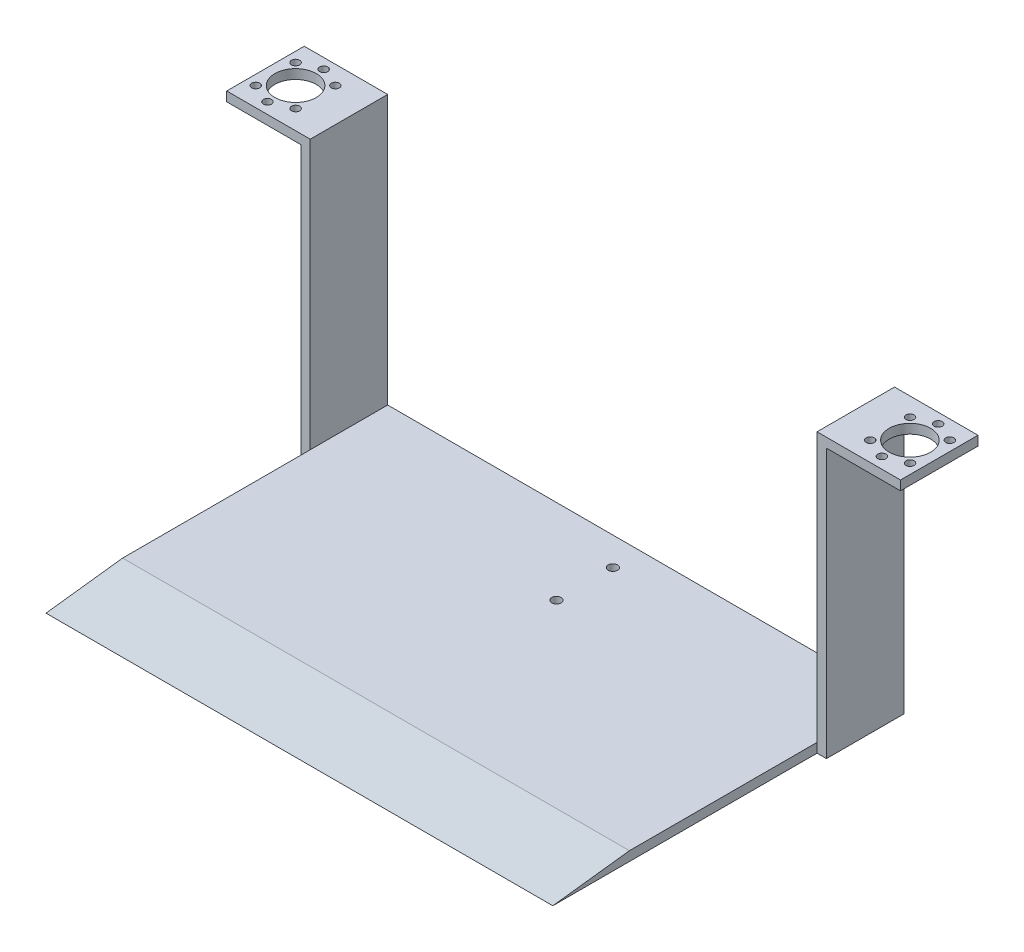
SolidWorks part; units mm, degrees
ref_plane "Front Plane" through (0, 0, 0) normal (0, 0, 1) x (1, 0, 0)
ref_plane "Top Plane" through (0, 0, 0) normal (0, 1, 0) x (1, 0, 0)
ref_plane "Right Plane" through (0, 0, 0) normal (1, 0, 0) x (0, 0, -1)
sketch "Sketch1" plane through (0, 0, 0) normal (0, 1, 0) x (1, 0, 0)
  line L1 (0, 0) -> (454.914, 0)
  line L2 (0, 0) -> (0, 381)
  line L3 (0, 381) -> (454.914, 381)
  line L4 (454.914, 0) -> (454.914, 381)
  dimension "D1" = 454.914
  dimension "D2" = 381
extrude "Boss-Extrude1" add sketch "Sketch1" along normal blind 187.96
sketch "Sketch3" plane through (0, 187.96, 0) normal (0, 1, 0) x (1, 0, 0)
  line L1 (454.914, 0) -> (404.9014, 0)
  line L2 (454.914, 0) -> (454.914, 202.0062)
  line L3 (454.914, 202.0062) -> (404.9014, 202.0062)
  line L4 (404.9014, 0) -> (404.9014, 202.0062)
  line L5 (0, 0) -> (50.0126, 0)
  line L6 (0, 0) -> (0, 202.0062)
  line L7 (0, 202.0062) -> (50.0126, 202.0062)
  line L8 (50.0126, 0) -> (50.0126, 202.0062)
  dimension "D1" = 202.0062
  dimension "D2" = 50.0126
  dimension "D3" = 202.0062
  dimension "D4" = 50.0126
extrude "Cut-Extrude1" cut sketch "Sketch3" against normal through all
sketch "Sketch4" plane through (0, 187.96, 0) normal (0, 1, 0) x (1, 0, 0)
  line L0 (454.914, 381) -> (0, 381) construction
  line L1 (0, 381) -> (0, 202.0062) construction
  line L2 (454.914, 202.0062) -> (454.914, 381) construction
  circle A0 centre (20.066, 355.092) radius 14
  circle A1 centre (434.848, 355.092) radius 14
  dimension "D1" = 28
  dimension "D4" = 28
  dimension "D5" = 20.066
  dimension "D6" = 25.908
  dimension "D2" = 25.908
  dimension "D3" = 20.066
extrude "Cut-Extrude2" cut sketch "Sketch4" against normal through all
sketch "Sketch5" plane through (0, 187.96, 0) normal (0, 1, 0) x (1, 0, 0)
  line L0 (454.914, 381) -> (0, 381) construction
  line L1 (56.3626, 381) -> (398.5514, 381)
  line L2 (56.3626, 381) -> (56.3626, 0)
  line L3 (56.3626, 0) -> (398.5514, 0)
  line L4 (398.5514, 381) -> (398.5514, 0)
  line L5 (50.0126, 0) -> (404.9014, 0) construction
  line L6 (50.0126, 0) -> (50.0126, 202.0062) construction
  line L7 (404.9014, 202.0062) -> (404.9014, 0) construction
  dimension "D1" = 6.35
  dimension "D2" = 6.35
extrude "Cut-Extrude3" cut sketch "Sketch5" against normal blind 181.61
sketch "Sketch6" plane through (454.914, 0, 0) normal (1, 0, 0) x (0, 0, -1)
  line L0 (381, 187.96) -> (381, 0) construction
  line L1 (202.0062, 0) -> (381, 0)
  line L2 (202.0062, 0) -> (202.0062, 181.5974)
  line L3 (202.0062, 181.5974) -> (381, 181.5974)
  line L4 (381, 0) -> (381, 181.5974)
  dimension "D1" = 181.5974
extrude "Cut-Extrude4" cut sketch "Sketch6" against normal blind 50.0126
sketch "Sketch7" plane through (0, 0, 0) normal (-1, 0, 0) x (0, 0, 1)
  line L0 (-202.0062, 0) -> (-202.0062, 187.96) construction
  line L1 (-381, 0) -> (-202.0062, 0)
  line L2 (-381, 0) -> (-381, 181.5974)
  line L3 (-381, 181.5974) -> (-202.0062, 181.5974)
  line L4 (-202.0062, 0) -> (-202.0062, 181.5974)
  dimension "D1" = 181.5974
extrude "Cut-Extrude5" cut sketch "Sketch7" against normal blind 50.0126
sketch "Sketch10" plane through (404.9014, 0, 0) normal (1, 0, 0) x (0, 0, -1)
  line L0 (0, 0) -> (202.0062, 0)
  line L1 (202.0062, 187.96) -> (0, 187.96) construction
  line L3 (202.0062, 187.96) -> (202.0062, 0)
  line L5 (381, 0) -> (0, 0) construction
  line L8 (202.0062, 187.96) -> (0, 187.96)
  line L9 (0, 187.96) -> (0, 0)
  line L10 (202.0062, 181.5974) -> (202.0062, 187.96) construction
extrude "Cut-Extrude6" cut sketch "Sketch10" against normal through all
sketch "Sketch11" plane through (0, 187.96, 0) normal (0, 1, 0) x (1, 0, 0)
  line L0 (434.848, 385.1807) -> (434.848, 325.1677) construction
  line L1 (457.9437, 355.092) -> (408.0384, 355.092) construction
  line L2 (434.848, 355.1742) -> (453.5332, 373.8594) construction
  line L3 (434.848, 355.1742) -> (419.9379, 370.0843) construction
  line L4 (434.848, 355.1742) -> (452.7645, 337.2577) construction
  line L5 (434.848, 355.1742) -> (417.2384, 337.5646) construction
  circle A1 centre (434.848, 374.1742) radius 2.75
  circle A2 centre (448.283, 368.6092) radius 2.75
  circle A3 centre (421.413, 368.6092) radius 2.75
  circle A4 centre (448.283, 341.7392) radius 2.75
  circle A5 centre (434.848, 336.1742) radius 2.75
  circle A6 centre (421.413, 341.7392) radius 2.75
  dimension "D2" = 45
  dimension "D5" = 5.5
  dimension "D6" = 5.5
  dimension "D7" = 5.5
  dimension "D8" = 5.5
  dimension "D9" = 5.5
  dimension "D10" = 5.5
  dimension "D3" = 45
  dimension "D4" = 45
extrude "Cut-Extrude7" cut sketch "Sketch11" against normal through all
sketch "Sketch12" plane through (0, 187.96, 0) normal (0, 1, 0) x (1, 0, 0)
  line L0 (20.066, 355.092) -> (20.066, 379.9549) construction
  line L1 (20.066, 355.092) -> (42.2706, 355.092) construction
  line L2 (20.066, 355.092) -> (20.066, 337.1345) construction
  line L3 (20.066, 355.092) -> (2.8652, 355.092) construction
  line L4 (20.066, 355.092) -> (38.3107, 373.3367) construction
  line L5 (20.066, 355.092) -> (33.6036, 341.5544) construction
  line L6 (20.066, 355.092) -> (5.5449, 369.6131) construction
  line L7 (20.066, 355.092) -> (7.0967, 342.1227) construction
  circle A1 centre (20.066, 374.092) radius 2.75
  circle A2 centre (6.631, 368.527) radius 2.75
  circle A3 centre (33.501, 368.527) radius 2.75
  circle A4 centre (33.501, 341.657) radius 2.75
  circle A5 centre (20.066, 336.092) radius 2.75
  circle A6 centre (6.631, 341.657) radius 2.75
  dimension "D5" = 5.5
  dimension "D6" = 5.5
  dimension "D7" = 5.5
  dimension "D8" = 5.5
  dimension "D9" = 5.5
  dimension "D10" = 5.5
  dimension "D1" = 45
  dimension "D2" = 45
  dimension "45" = 45
  dimension "D3" = 45
extrude "Cut-Extrude8" cut sketch "Sketch12" against normal through all
sketch "Sketch13" plane through (398.5514, 0, 0) normal (1, 0, 0) x (0, 0, -1)
  line L0 (202.0062, 0) -> (150.2896, 0)
  line L1 (150.2896, 0) -> (202.0062, 6.35)
  line L2 (202.0062, 0) -> (202.0062, 181.5974) construction
  line L3 (202.0062, 6.35) -> (202.0062, 0)
  dimension "D1" = 7
  dimension "D2" = 6.35
extrude "Boss-Extrude2" add sketch "Sketch13" against normal up to surface (342.1888 mm away) up to face at (56.3626, 97.155, -291.5031)
sketch "Sketch15" plane through (0, 187.96, 0) normal (0, 1, 0) x (1, 0, 0)
  line L0 (398.5514, 328.676) -> (454.914, 328.676) construction
  line L1 (398.5514, 202.0062) -> (398.5514, 381) construction
  line L2 (454.914, 202.0062) -> (454.914, 381) construction
  line L3 (454.914, 381) -> (398.5514, 381) construction
  line L4 (0, 328.676) -> (56.3626, 328.676) construction
  line L5 (398.5514, 328.676) -> (454.914, 328.676)
  line L6 (398.5514, 328.676) -> (398.5514, 202.0062)
  line L7 (398.5514, 202.0062) -> (454.914, 202.0062)
  line L8 (454.914, 328.676) -> (454.914, 202.0062)
  line L9 (0, 381) -> (0, 202.0062) construction
  line L10 (56.3626, 381) -> (56.3626, 202.0062) construction
  line L11 (56.3626, 381) -> (0, 381) construction
  line L13 (56.3626, 202.0062) -> (0, 202.0062)
  line L14 (56.3626, 202.0062) -> (56.3626, 328.676)
  line L15 (56.3626, 328.676) -> (0, 328.676)
  line L16 (0, 202.0062) -> (0, 328.676)
  dimension "D1" = 52.324
  dimension "D2" = 52.324
extrude "Cut-Extrude9" cut sketch "Sketch15" against normal through all
sketch "Sketch16" plane through (0, 0, 0) normal (0, -1, 0) x (1, 0, 0)
  line L0 (227.457, -381) -> (227.457, -253.5221) construction
  line L1 (404.9014, -381) -> (50.0126, -381) construction
  circle A0 centre (227.457, -361.95) radius 3.175
  circle A1 centre (227.457, -323.85) radius 3.175
  point P8 (0, 0)
  point P9 (0, 0)
  dimension "D1" = 6.35
  dimension "D2" = 6.35
  dimension "D3" = 38.1
  dimension "D4" = 19.05
extrude "Cut-Extrude10" cut sketch "Sketch16" against normal through all
